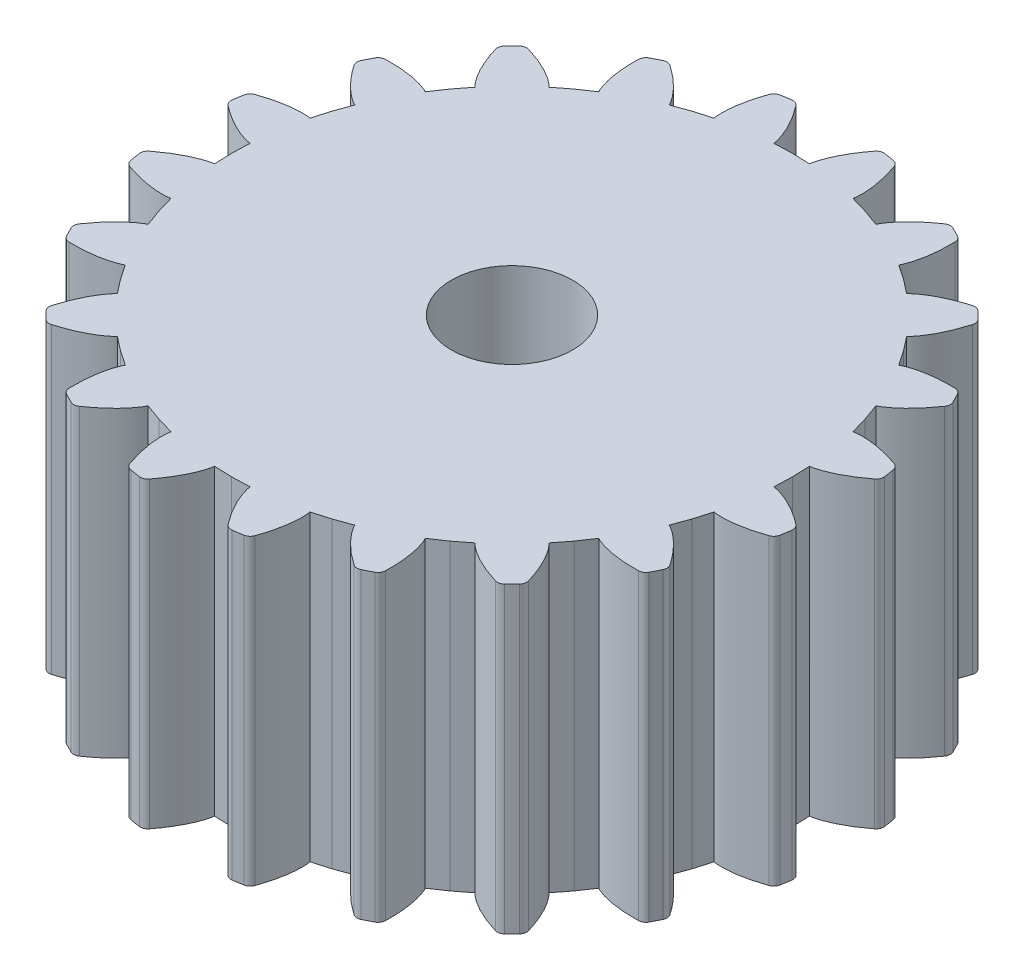
SolidWorks part; units mm, degrees
ref_plane "Front Plane" through (0, 0, 0) normal (0, 0, 1) x (1, 0, 0)
ref_plane "Top Plane" through (0, 0, 0) normal (0, 1, 0) x (1, 0, 0)
ref_plane "Right Plane" through (0, 0, 0) normal (1, 0, 0) x (0, 0, -1)
sketch "Sketch1" plane through (0, 0, 0) normal (0, 1, 0) x (1, 0, 0)
  circle A0 centre (0, 0) radius 11.049
  dimension "D1" = 22.098
extrude "Boss-Extrude1" add sketch "Sketch1" along normal blind 10.16 contours A0
sketch "Sketch2" plane through (0, 10.16, 0) normal (0, 1, 0) x (1, 0, 0)
  circle A0 centre (0, 0) radius 2.032
  dimension "D1" = 4.064
extrude "Cut-Extrude1" cut sketch "Sketch2" against normal through all
sketch "Sketch3" plane through (0, 10.16, 0) normal (0, 1, 0) x (1, 0, 0)
  line L0 (0, 0) -> (14.4656, 0) construction
  circle A0 centre (0, 0) radius 10.033 construction
  circle A1 centre (0, 0) radius 9.398 construction
  circle A2 centre (0, 0) radius 8.89 construction
  arc A3 (9.3779, 0.5976) -> (9.398, 0) centre (-59.9606, -2.0331) cw
  arc A4 (10.9135, 1.3768) -> (11.0365, 1.4747) centre (10.1343, 2.4822) ccw
  arc A7 (10.9135, -1.3768) -> (11.0365, -1.4747) centre (10.1343, -2.4822) cw
  arc A8 (9.3779, -0.5976) -> (9.398, 0) centre (-59.9606, 2.0331) ccw
  arc A9 (11.0365, -1.4747) -> (11.0365, 1.4747) centre (7.9833, 0) ccw
  spline S0 degree 4 poles (9.3779, 0.5976) (9.3805, 0.5978) (9.3877, 0.5984) (9.4098, 0.6011) (9.4533, 0.6082) (9.5067, 0.6197) (9.5678, 0.6354) (9.6264, 0.6526) (9.6763, 0.6685) (9.7258, 0.6855) (9.775, 0.7034) (9.8343, 0.7264) (9.9051, 0.7556) (9.9872, 0.7922) (10.0797, 0.8366) (10.1732, 0.8848) (10.2645, 0.9348) (10.3559, 0.9882) (10.4438, 1.0418) (10.5341, 1.1004) (10.6171, 1.156) (10.709, 1.2214) (10.7829, 1.2752) (10.8792, 1.3494) (10.9357, 1.3943) (11.0014, 1.4479) (11.0304, 1.4723) (11.0482, 1.4873) knots 0 0 0 0 0 0.005377 0.015084 0.04661 0.092111 0.119476 0.146842 0.174209 0.201575 0.228941 0.256307 0.307035 0.361767 0.4165 0.471232 0.525964 0.580697 0.635429 0.690161 0.744894 0.799626 0.854358 0.909091 0.954545 1 1 1 1 1 construction
  spline S1 degree 4 poles (9.3779, 0.5976) (9.3805, 0.5978) (9.3877, 0.5984) (9.4098, 0.6011) (9.4533, 0.6082) (9.5067, 0.6197) (9.5678, 0.6354) (9.6264, 0.6526) (9.6763, 0.6685) (9.7258, 0.6855) (9.775, 0.7034) (9.8343, 0.7264) (9.9051, 0.7556) (9.9872, 0.7922) (10.0797, 0.8366) (10.1732, 0.8848) (10.2645, 0.9348) (10.3559, 0.9882) (10.4438, 1.0418) (10.5341, 1.1004) (10.6171, 1.156) (10.709, 1.2214) (10.7829, 1.2752) (10.8583, 1.3333) (10.8949, 1.362) (10.9135, 1.3768) knots 0 0 0 0 0 0.005377 0.015084 0.04661 0.092111 0.119476 0.146842 0.174209 0.201575 0.228941 0.256307 0.307035 0.361767 0.4165 0.471232 0.525964 0.580697 0.635429 0.690161 0.744894 0.799626 0.854358 0.909091 0.909091 0.909091 0.909091 0.909091
  spline S2 degree 4 poles (9.3779, -0.5976) (9.3805, -0.5978) (9.3877, -0.5984) (9.4098, -0.6011) (9.4533, -0.6082) (9.5067, -0.6197) (9.5678, -0.6354) (9.6264, -0.6526) (9.6763, -0.6685) (9.7258, -0.6855) (9.775, -0.7034) (9.8343, -0.7264) (9.9051, -0.7556) (9.9872, -0.7922) (10.0797, -0.8366) (10.1732, -0.8848) (10.2645, -0.9348) (10.3559, -0.9882) (10.4438, -1.0418) (10.5341, -1.1004) (10.6171, -1.156) (10.709, -1.2214) (10.7829, -1.2752) (10.8583, -1.3333) (10.8949, -1.362) (10.9135, -1.3768) knots 0 0 0 0 0 0.005377 0.015084 0.04661 0.092111 0.119476 0.146842 0.174209 0.201575 0.228941 0.256307 0.307035 0.361767 0.4165 0.471232 0.525964 0.580697 0.635429 0.690161 0.744894 0.799626 0.854358 0.909091 0.909091 0.909091 0.909091 0.909091
  dimension "D1" = 20.066
  dimension "D2" = 18.796
  dimension "D3" = 17.78
extrude "Cut-Extrude2" cut sketch "Sketch3" against normal through all
fillet "Fillet1" radius 0.254 2 edges at (10.9587, 5.08, 1.4101) (10.9587, 5.08, -1.4101)
pattern_circular "CirPattern1" count 20 over 360 about axis through (0, 10.16, 0) along (0, 1, 0) of "Fillet1", "Cut-Extrude2"
equation "\"P\"= 25.4'INPUT: diameteral pitch"
equation "\"z\"= 20'INPUT: number of teeth"
equation "\"a\"= 20'INPUT: pressure angle, degrees"
equation "\"s\"= 0.4'INPUT: face width (inches)"
equation "\"D_b\"= 0.16'INPUT: gear bore diameter (inches)"
equation "\"c\"= 0.157 / \"P\"'clearance"
equation "\"D_p\"= \"z\" / \"P\"'pitch circle diameter"
equation "\"D_base\"= \"D_p\" * cos ( \"a\" )'base circle diameter"
equation "\"h_a\"= 1 / \"P\"'addendum depth"
equation "\"h_d\"= 1 / \"P\" + \"c\"'dedendum depth"
equation "\"P_c\"= pi / \"P\"'circular pitch"
equation "\"D_a\"= \"D_p\" + ( 2 * \"h_a\" )'addendum diameter"
equation "\"D_d\" = \"D_p\" - ( 2 * \"h_d\" )'dedendum diameter"
equation "\"theta\"= 360 / \"z\"'pitch angle"
equation "\"a_inv\"= ( \"D_p\" ^ 2 - \"D_base\" ^ 2 ) ^ 0.5 / \"D_base\" * 180 / pi - \"a\"'alpha angle for involute curve"
equation "\"b_inv\"= ( \"theta\" / 4 - \"a_inv\" )'beta angle (parameter for ivolute curve parameterization)"
equation "\"zeta\"= ( ( \"D_a\" / 2 ) ^ 2 - ( \"D_base\" / 2 ) ^ 2 ) ^ 0.5 / ( \"D_base\" / 2 )'zeta (domain for involute curve equation)"
